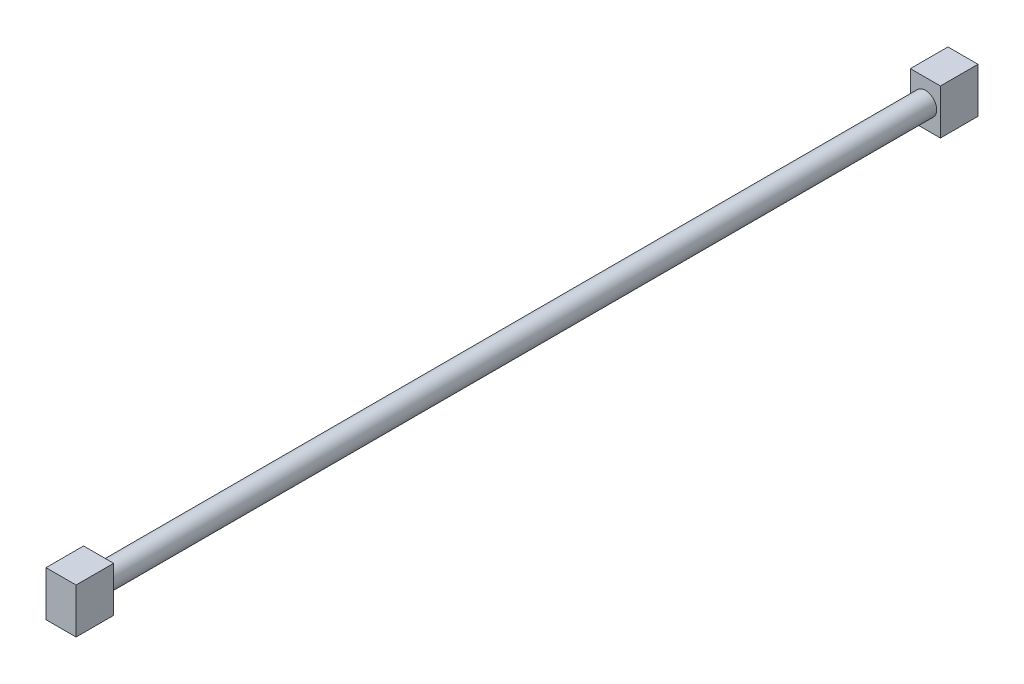
SolidWorks part; units mm, degrees
material "1350 Alloy"
ref_plane "Front Plane" through (0, 0, 0) normal (0, 0, 1) x (1, 0, 0)
ref_plane "Top Plane" through (0, 0, 0) normal (0, 1, 0) x (1, 0, 0)
ref_plane "Right Plane" through (0, 0, 0) normal (1, 0, 0) x (0, 0, -1)
sketch "Sketch2" plane through (0, 0, 0) normal (0, 0, 1) x (1, 0, 0)
  line L1 (-2.54, -3.81) -> (2.54, -3.81)
  line L2 (-2.54, -3.81) -> (-2.54, 3.81)
  line L3 (-2.54, 3.81) -> (2.54, 3.81)
  line L4 (2.54, -3.81) -> (2.54, 3.81)
  line L5 (-2.54, -3.81) -> (2.54, 3.81) construction
  line L6 (-2.54, 3.81) -> (2.54, -3.81) construction
  point P0 (0, 0)
  dimension "D1" = 5.08
  dimension "D2" = 7.62
extrude "Boss-Extrude1" add sketch "Sketch2" along normal blind 6.35
sketch "Sketch3" plane through (0, 0, 6.35) normal (0, 0, 1) x (1, 0, 0)
  circle A0 centre (0, 0) radius 1.905
  dimension "D1" = 3.81
extrude "Boss-Extrude2" add sketch "Sketch3" along normal blind 139.7
sketch "Sketch4" plane through (0, 0, 146.05) normal (0, 0, 1) x (1, 0, 0)
  line L1 (-2.54, -3.81) -> (2.54, -3.81)
  line L2 (-2.54, -3.81) -> (-2.54, 3.81)
  line L3 (-2.54, 3.81) -> (2.54, 3.81)
  line L4 (2.54, -3.81) -> (2.54, 3.81)
  line L5 (-2.54, -3.81) -> (2.54, 3.81) construction
  line L6 (-2.54, 3.81) -> (2.54, -3.81) construction
  point P0 (0, 0)
  dimension "D1" = 5.08
  dimension "D2" = 7.62
extrude "Boss-Extrude3" add sketch "Sketch4" along normal blind 6.35
